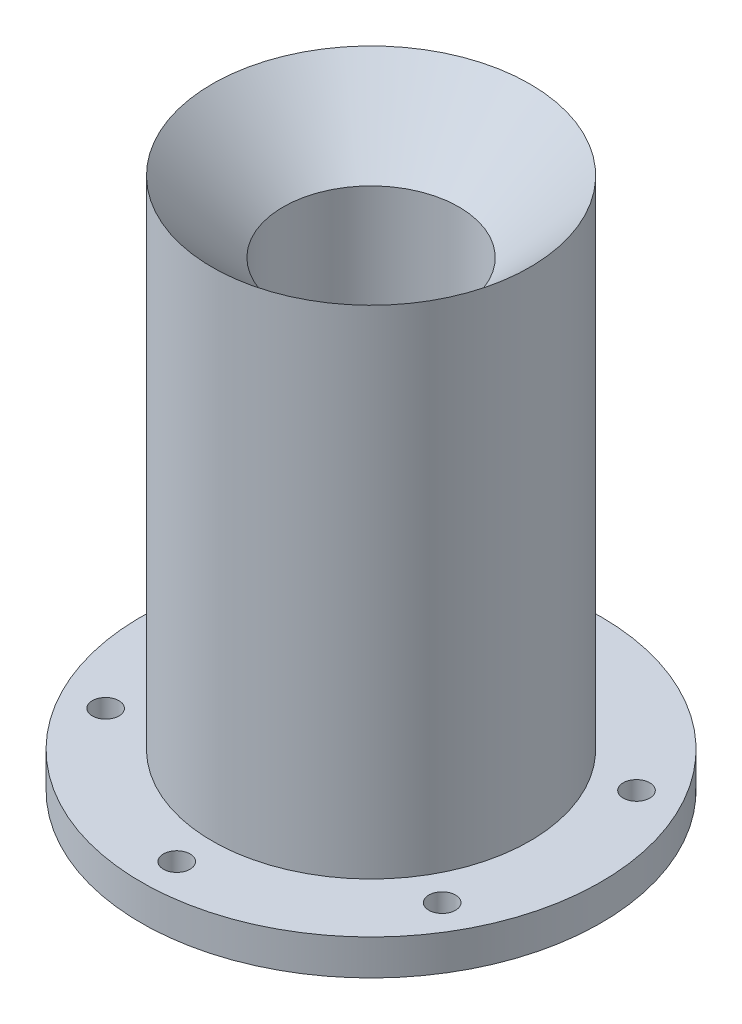
SolidWorks part; units mm, degrees
ref_plane "Спереди" through (0, 0, 0) normal (0, 0, 1) x (1, 0, 0)
ref_plane "Сверху" through (0, 0, 0) normal (0, 1, 0) x (1, 0, 0)
ref_plane "Справа" through (0, 0, 0) normal (1, 0, 0) x (0, 0, -1)
sketch "Эскиз1" plane through (0, 0, 0) normal (1, 0, 0) x (0, 0, -1)
  line L0 (0, 0) -> (0, 13259.4021) construction
  line L1 (9.9, 52) -> (9.9, 2)
  line L6 (9.9, 2) -> (15, 2)
  line L7 (15, 2) -> (15, 0)
  line L11 (15, 0) -> (25.9, 0)
  line L16 (17.9, 60) -> (17.9, 4)
  line L17 (17.9, 4) -> (25.9, 4)
  line L18 (25.9, 4) -> (25.9, 0)
  line L22 (17.9, 60) -> (9.9, 52)
  dimension "D2" = 2
  dimension "D4" = 50
  dimension "D5" = 8
  dimension "D3" = 15
  dimension "D6" = 45
  dimension "D7" = 8
  dimension "D8" = 4
  dimension "D1" = 19.8
revolve "Повернуть1" add sketch "Эскиз1" angle 360 about L0
sketch "Эскиз2" plane through (0, 4, 0) normal (0, 1, 0) x (1, 0, 0)
  line L0 (0, 25.9) -> (0, 17.9) construction
  circle A0 centre (0, 0) radius 25.9 construction
  circle A1 centre (0, 0) radius 17.9 construction
  circle A2 centre (0, 21.9) radius 1.5
  circle A3 centre (18.966, 10.95) radius 1.5
  circle A4 centre (18.966, -10.95) radius 1.5
  circle A5 centre (0, -21.9) radius 1.5
  circle A6 centre (-18.966, -10.95) radius 1.5
  circle A7 centre (-18.966, 10.95) radius 1.5
  point P21 (0, 0)
  dimension "D2" = 3
  dimension "D1" = 6
extrude "Вырез-Вытянуть1" cut sketch "Эскиз2" against normal blind 10 contours A2
equation "\"D4@Эскиз1\"=30+20"
equation "\"D1@Эскиз1\"=11.8+4*2"
